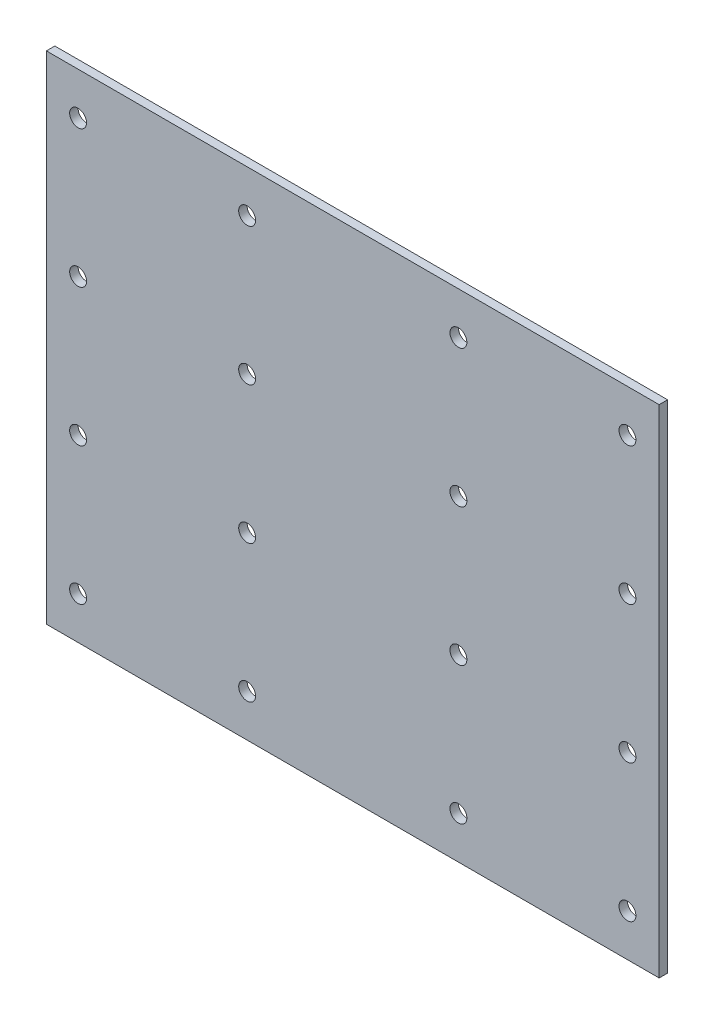
SolidWorks part; units mm, degrees
ref_plane "Front Plane" through (0, 0, 0) normal (0, 0, 1) x (1, 0, 0)
ref_plane "Top Plane" through (0, 0, 0) normal (0, 1, 0) x (1, 0, 0)
ref_plane "Right Plane" through (0, 0, 0) normal (1, 0, 0) x (0, 0, -1)
sketch "Sketch1" plane through (0, 0, 0) normal (0, 0, 1) x (1, 0, 0)
  line L1 (0, 0) -> (184.15, 0)
  line L2 (0, 0) -> (0, -149.225)
  line L3 (0, -149.225) -> (184.15, -149.225)
  line L4 (184.15, 0) -> (184.15, -149.225)
  dimension "D1" = 184.15
  dimension "D2" = 149.225
extrude "Boss-Extrude1" add sketch "Sketch1" along normal blind 2.54
sketch "Sketch2" plane through (0, 0, 2.54) normal (0, 0, 1) x (1, 0, 0)
  line L0 (184.15, 0) -> (0, 0) construction
  line L1 (0, 0) -> (0, -149.225) construction
  circle A0 centre (9.525, -12.7) radius 2.54
  dimension "D1" = 5.08
  dimension "D2" = 12.7
  dimension "D3" = 9.525
extrude "Cut-Extrude1" cut sketch "Sketch2" against normal blind 2.54
pattern_linear "LPattern1" count 2 spacing 50.8 along (1, 0, 0) of "Cut-Extrude1"
pattern_linear "LPattern2" count 2 spacing 41.275 along (0, -1, 0) of "LPattern1", "Cut-Extrude1"
sketch "Sketch3" plane through (0, 0, 2.54) normal (0, 0, 1) x (1, 0, 0)
  circle A0 centre (123.825, -12.7) radius 2.54
  circle A1 centre (60.325, -12.7) radius 2.54 construction
  dimension "D1" = 5.08
  dimension "D2" = 63.5
extrude "Cut-Extrude2" cut sketch "Sketch3" against normal blind 2.54
pattern_linear "LPattern3" count 2 spacing 50.8 along (1, 0, 0) of "Cut-Extrude2"
pattern_linear "LPattern4" count 2 spacing 41.275 along (0, -1, 0) of "LPattern3", "Cut-Extrude2"
sketch "Sketch5" plane through (0, 0, 2.54) normal (0, 0, 1) x (1, 0, 0)
  line L0 (0, 0) -> (0, -149.225) construction
  line L1 (0, -149.225) -> (184.15, -149.225) construction
  circle A0 centre (9.525, -136.525) radius 2.54
  dimension "D1" = 5.08
  dimension "D2" = 9.525
  dimension "D3" = 12.7
extrude "Cut-Extrude4" cut sketch "Sketch5" against normal blind 2.54
pattern_linear "LPattern7" count 2 spacing 41.275 along (0, 1, 0) of "Cut-Extrude4"
pattern_linear "LPattern8" count 2 spacing 50.8 along (1, 0, 0) of "LPattern7", "Cut-Extrude4"
pattern_linear "LPattern9" count 2 spacing 82.55 along (0, -1, 0) of "LPattern4", "Cut-Extrude2", "LPattern3"
